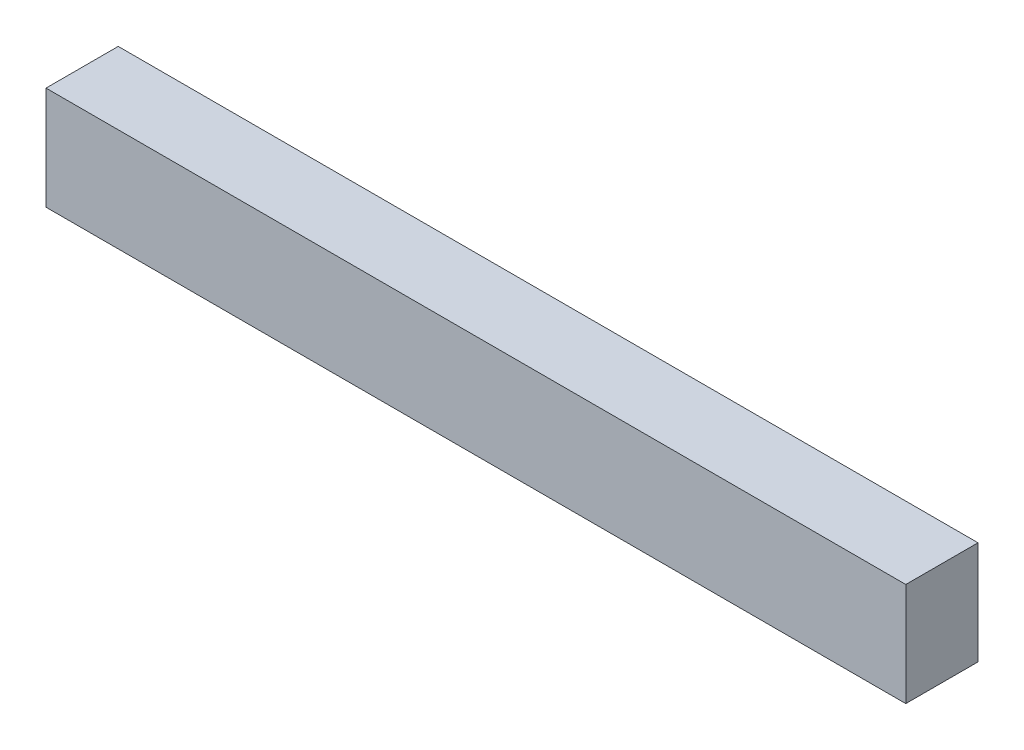
SolidWorks part; units mm, degrees
ref_plane "Front Plane" through (0, 0, 0) normal (0, 0, 1) x (1, 0, 0)
ref_plane "Top Plane" through (0, 0, 0) normal (0, 1, 0) x (1, 0, 0)
ref_plane "Right Plane" through (0, 0, 0) normal (1, 0, 0) x (0, 0, -1)
sketch "Sketch1" plane through (0, 0, 0) normal (0, 0, 1) x (1, 0, 0)
  line L1 (-49.7008, 13.5095) -> (13.7992, 13.5095)
  line L2 (-49.7008, 13.5095) -> (-49.7008, 5.8895)
  line L3 (-49.7008, 5.8895) -> (13.7992, 5.8895)
  line L4 (13.7992, 13.5095) -> (13.7992, 5.8895)
  dimension "D1" = 63.5
  dimension "D2" = 7.62
extrude "Boss-Extrude1" add sketch "Sketch1" along normal blind 5.334
equation "\"MDF\"= .21in"
equation "\"Foamcore\"= .13in"
equation "\"Gmaterial\"= \"MDF\""
equation "\"D1@Boss-Extrude1\"=\"MDF\""
